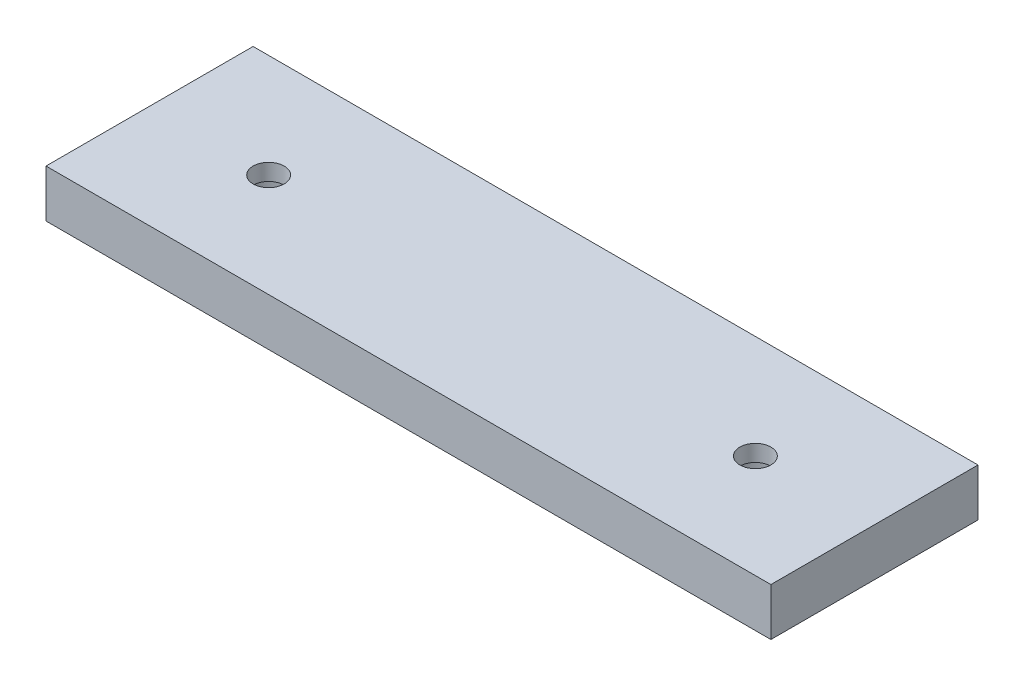
SolidWorks part; units mm, degrees
material "2219-O"
ref_plane "Front Plane" through (0, 0, 0) normal (0, 0, 1) x (1, 0, 0)
ref_plane "Top Plane" through (0, 0, 0) normal (0, 1, 0) x (1, 0, 0)
ref_plane "Right Plane" through (0, 0, 0) normal (1, 0, 0) x (0, 0, -1)
sketch "Çizim1" plane through (0, 0, 0) normal (0, 1, 0) x (1, 0, 0)
  line L1 (0, 0) -> (70, 0)
  line L2 (0, 0) -> (0, 20)
  line L3 (0, 20) -> (70, 20)
  line L4 (70, 0) -> (70, 20)
  dimension "D1" = 20
  dimension "D2" = 70
extrude "Yükseklik-Ekstrüzyon1" add sketch "Çizim1" along normal blind 4.6
sketch "Çizim2" plane through (0, 0, 0) normal (0, -1, 0) x (1, 0, 0)
  line L0 (70, -10) -> (60, -10) construction
  line L1 (70, 0) -> (70, -20) construction
  line L2 (57, -10) -> (60, -10) construction
  line L3 (35, 0) -> (35, -20) construction
  line L4 (0, 0) -> (70, 0) construction
  line L5 (70, -20) -> (0, -20) construction
  line L6 (0, -10) -> (10, -10) construction
  circle A0 centre (58.5, -10) radius 1.5
  circle A1 centre (11.5, -10) radius 1.5
  dimension "D1" = 3
  dimension "D2" = 10
extrude "Kes-Ekstrüzyon1" cut sketch "Çizim2" against normal up to surface (4.6 mm away) up to face at (35, 4.6, -10)
sketch "Çizim3" plane through (0, 0, 0) normal (0, -1, 0) x (1, 0, 0)
  circle A0 centre (11.5, -10) radius 3
  circle A1 centre (58.5, -10) radius 3
  dimension "D1" = 6
  dimension "D2" = 6
extrude "Kes-Ekstrüzyon2" cut sketch "Çizim3" against normal blind 3
